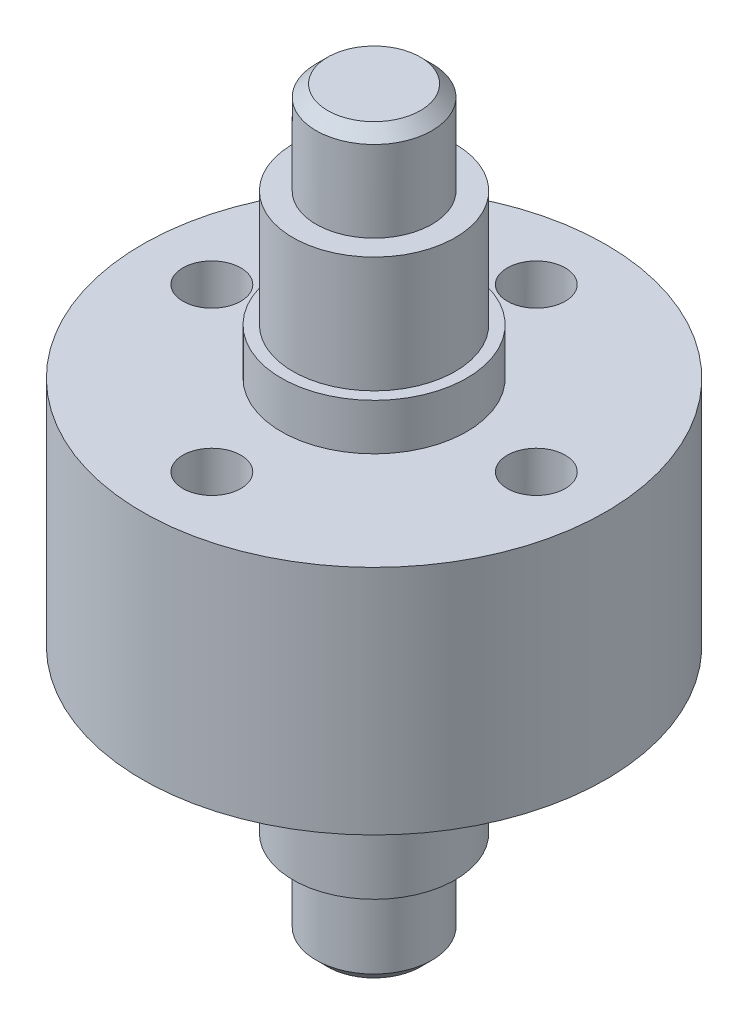
SolidWorks part; units mm, degrees
material "6061-T6 (SS)"
ref_plane "前视基准面" through (0, 0, 0) normal (0, 0, 1) x (1, 0, 0)
ref_plane "上视基准面" through (0, 0, 0) normal (0, 1, 0) x (1, 0, 0)
ref_plane "右视基准面" through (0, 0, 0) normal (1, 0, 0) x (0, 0, -1)
sketch "草图1" plane through (0, 0, 0) normal (0, 0, 1) x (1, 0, 0)
  line L0 (0, 0) -> (0, 32) construction
  line L1 (0, 0) -> (0, 32)
  line L2 (0, 32) -> (2.5, 32)
  line L3 (3.5, 28) -> (3.5, 23)
  line L4 (3.5, 23) -> (4, 23)
  line L5 (4, 23) -> (4, 21)
  line L6 (4, 21) -> (10, 21)
  line L7 (10, 21) -> (10, 11)
  line L8 (10, 11) -> (4, 11)
  line L9 (4, 11) -> (4, 9)
  line L10 (4, 9) -> (3.5, 9)
  line L11 (3.5, 9) -> (3.5, 4)
  line L12 (2.5, 0) -> (0, 0)
  line L13 (2.5, 32) -> (2.5, 28)
  line L14 (2.5, 28) -> (3.5, 28)
  line L15 (2.5, 0) -> (2.5, 4)
  line L16 (2.5, 4) -> (3.5, 4)
  point P15 (10, 21.187)
  dimension "D1" = 5
  dimension "D2" = 7
  dimension "D3" = 8
  dimension "D4" = 10
  dimension "D5" = 32
  dimension "D6" = 2
  dimension "D7" = 20
  dimension "D8" = 2.5
revolve "旋转1" add sketch "草图1" angle 360 about L0
hole_wizard "M3 螺纹孔1" positions "草图3" profile "草图4" tap size "M3" standard "GB" end condition through all
sketch "草图3" plane through (0, 21, 0) normal (0, 1, 0) x (1, 0, 0)
  circle A0 centre (0, 0) radius 7
  point P0 (0, 7)
  point P2 (7, 0)
  point P4 (0, -7)
  point P6 (-7, 0)
  dimension "D1" = 14
sketch "草图4" plane through (0, 21, -7) normal (1, 0, 0) x (0, 0, 1)
  line L0 (0, 0) -> (0, 21)
  line L1 (0, 21) -> (1.25, 21)
  line L2 (1.25, 21) -> (1.25, 0)
  line L5 (1.25, 0) -> (0, 0)
  line L11 (0, -6.35) -> (0, 107.95) construction
  dimension "通孔螺纹孔钻头直径" = 2.5
  dimension "通孔螺纹孔钻头深度" = 21
cosmetic thread "孔螺蚊线1" parameters "D2"=3
cosmetic thread "孔螺蚊线2" parameters "D2"=3
cosmetic thread "孔螺蚊线3" parameters "D2"=3
cosmetic thread "孔螺蚊线4" parameters "D2"=3
chamfer "倒角1" distance 0.5 angle 45 2 edges at (0, 32, -2.5) (0, 0, -2.5)
